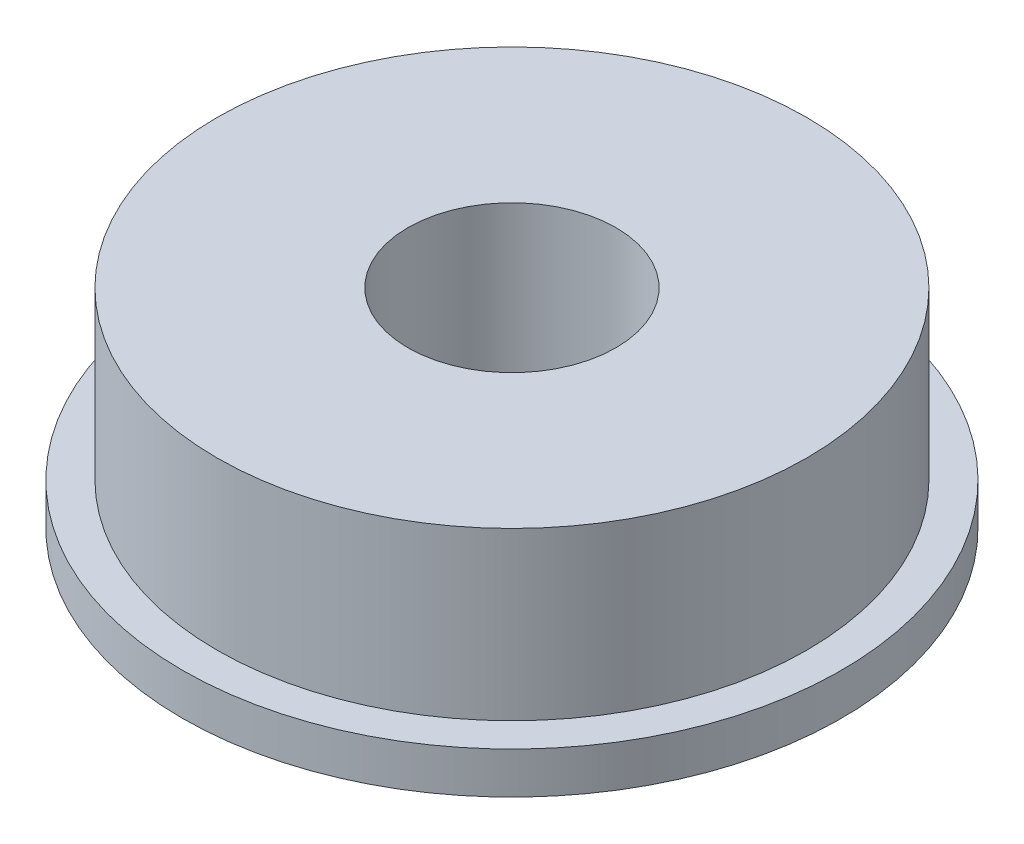
SolidWorks part; units mm, degrees
material "AISI 1020 钢，冷轧"
ref_plane "前视基准面" through (0, 0, 0) normal (0, 0, 1) x (1, 0, 0)
ref_plane "上视基准面" through (0, 0, 0) normal (0, 1, 0) x (1, 0, 0)
ref_plane "右视基准面" through (0, 0, 0) normal (1, 0, 0) x (0, 0, -1)
other "Configuration Table"
sketch "草图1" plane through (0, 0, 0) normal (0, 1, 0) x (1, 0, 0)
  circle A0 centre (0, 0) radius 9.5
  dimension "D1" = 19
extrude "凸台-拉伸1" add sketch "草图1" along normal blind 1.2
sketch "草图2" plane through (0, 1.2, 0) normal (0, 1, 0) x (1, 0, 0)
  circle A0 centre (0, 0) radius 8.5
  dimension "D1" = 17
extrude "凸台-拉伸2" add sketch "草图2" along normal blind 4.8
sketch "草图3" plane through (0, 6, 0) normal (0, 1, 0) x (1, 0, 0)
  circle A0 centre (0, 0) radius 3
  dimension "D1" = 6
extrude "切除-拉伸1" cut sketch "草图3" against normal blind 20
